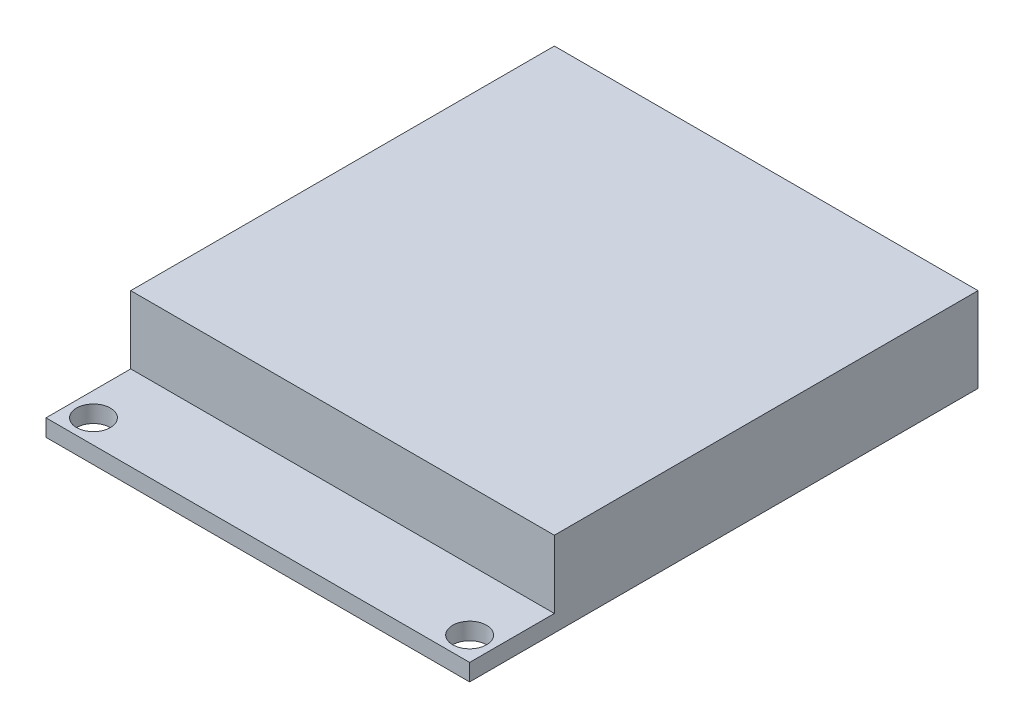
SolidWorks part; units mm, degrees
ref_plane "前视基准面" through (0, 0, 0) normal (0, 0, 1) x (1, 0, 0)
ref_plane "上视基准面" through (0, 0, 0) normal (0, 1, 0) x (1, 0, 0)
ref_plane "右视基准面" through (0, 0, 0) normal (1, 0, 0) x (0, 0, -1)
other "Configuration Table"
sketch "草图1" plane through (0, 0, 0) normal (0, 1, 0) x (1, 0, 0)
  line L1 (-12.5, -15) -> (12.5, -15)
  line L2 (-12.5, -15) -> (-12.5, 15)
  line L3 (-12.5, 15) -> (12.5, 15)
  line L4 (12.5, -15) -> (12.5, 15)
  line L5 (0, 15) -> (0, -15) construction
  line L6 (-12.5, 0) -> (12.5, 0) construction
  point P0 (0, 0)
  dimension "D1" = 25
  dimension "D2" = 30
extrude "凸台-拉伸1" add sketch "草图1" along normal blind 1
sketch "草图2" plane through (0, 1, 0) normal (0, 1, 0) x (1, 0, 0)
  line L0 (12.5, -15) -> (12.5, 15) construction
  line L1 (-12.5, 15) -> (12.5, 15)
  line L2 (-12.5, 15) -> (-12.5, -10)
  line L3 (-12.5, -10) -> (12.5, -10)
  line L4 (12.5, 15) -> (12.5, -10)
  dimension "D1" = 25
extrude "凸台-拉伸2" add sketch "草图2" along normal blind 4
sketch "草图3" plane through (0, 1, 0) normal (0, 1, 0) x (1, 0, 0)
  line L0 (-12.5, -15) -> (12.5, -15) construction
  line L1 (-12.5, -10) -> (-12.5, -15) construction
  line L2 (12.5, -15) -> (12.5, -10) construction
  circle A0 centre (-11.1, -13.6) radius 1
  circle A1 centre (11.1, -13.6) radius 1
  point P8 (0, 0)
  dimension "D1" = 2
  dimension "D2" = 1.4
  dimension "D3" = 1.4
  dimension "D4" = 1.4
extrude "切除-拉伸1" cut sketch "草图3" against normal up to surface (1 mm away) up to face at (0, 0, 0)
